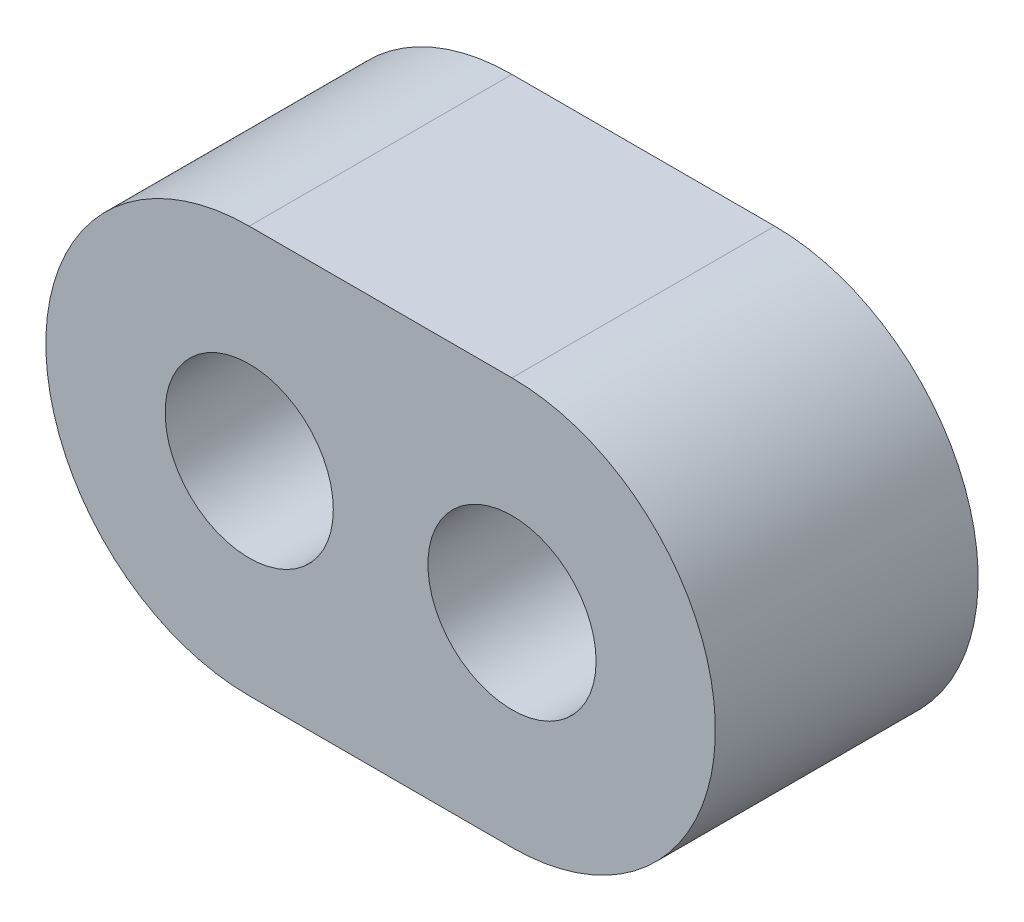
SolidWorks part; units mm, degrees
ref_plane "前视基准面" through (0, 0, 0) normal (0, 0, 1) x (1, 0, 0)
ref_plane "上视基准面" through (0, 0, 0) normal (0, 1, 0) x (1, 0, 0)
ref_plane "右视基准面" through (0, 0, 0) normal (1, 0, 0) x (0, 0, -1)
other "Configuration Table"
sketch "草图1" plane through (0, 0, 0) normal (0, 0, 1) x (1, 0, 0)
  line L0 (0, 0) -> (5, 0) construction
  line L1 (0, 3.8697) -> (5, 3.8697)
  line L2 (0, -3.8697) -> (5, -3.8697)
  arc A0 (0, 3.8697) -> (0, -3.8697) centre (0, 0) ccw
  arc A1 (5, -3.8697) -> (5, 3.8697) centre (5, 0) ccw
  circle A2 centre (0, 0) radius 1.6
  circle A3 centre (5, 0) radius 1.6
  point P3 (2.5, 0)
  dimension "D1" = 3.2
  dimension "D2" = 3.2
  dimension "D3" = 5
extrude "凸台-拉伸1" add sketch "草图1" along normal blind 5
